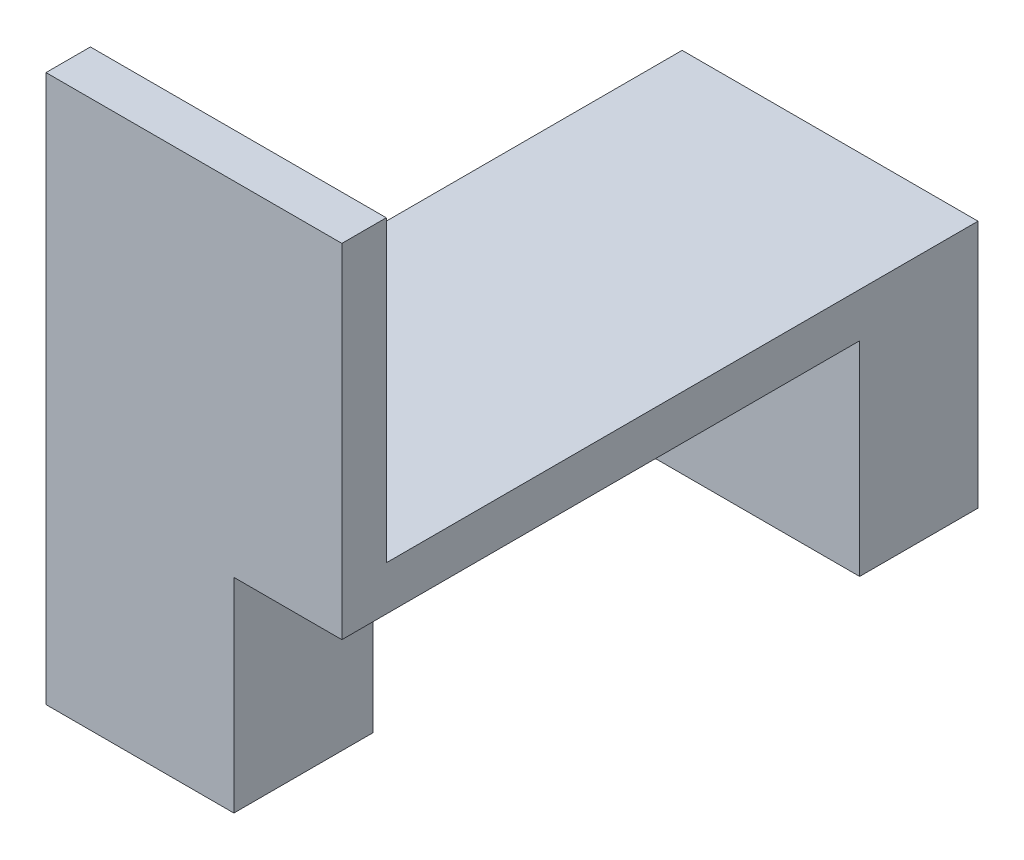
SolidWorks part; units mm, degrees
ref_plane "Спереди" through (0, 0, 0) normal (0, 0, 1) x (1, 0, 0)
ref_plane "Сверху" through (0, 0, 0) normal (0, 1, 0) x (1, 0, 0)
ref_plane "Справа" through (0, 0, 0) normal (1, 0, 0) x (0, 0, -1)
sketch "Эскиз3" plane through (0, 0, 0) normal (1, 0, 0) x (0, 0, -1)
  line L0 (0, 0) -> (-21.5, 0)
  line L1 (-21.5, 0) -> (-21.5, 11.6)
  line L2 (0, 1.5) -> (-20, 1.5)
  line L3 (-20, 1.5) -> (-20, 11.6)
  line L4 (-21.5, 11.6) -> (-20, 11.6)
  line L5 (0, 1.5) -> (0, 0)
  line L6 (-66.5, 11.6) -> (-13.06, 11.6) construction
  point P2 (-21.5, 11.6)
  dimension "D2" = 20
  dimension "D3" = 1.5
extrude "Бобышка-Вытянуть3" add sketch "Эскиз3" against normal blind 10
sketch "Эскиз4" plane through (0, 0, 0) normal (0, 1, 0) x (1, 0, 0)
  line L0 (-10, 0) -> (0, 0) construction
  line L1 (-10, -21.5) -> (-7.5, -21.5)
  line L2 (-10, -21.5) -> (-10, 0)
  line L3 (-10, 0) -> (-7.5, 0)
  line L4 (-7.5, -21.5) -> (-7.5, 0)
  line L5 (-7.3, -4) -> (-7.3, -16.8) construction
  line L6 (-10, -10.75) -> (0, -10.75) construction
  line L7 (0, 0) -> (0, -20) construction
  point P7 (-7.5, -10.75)
  dimension "D1" = 0.2
extrude "Бобышка-Вытянуть4" add sketch "Эскиз4" against normal blind 1.5
sketch "Эскиз5" plane through (0, 0, 0) normal (0, 1, 0) x (1, 0, 0)
  line L0 (0, -4) -> (-7.3, -4) construction
  line L1 (-7.5, 0) -> (-3.65, 0)
  line L2 (-7.5, 0) -> (-7.5, -4) construction
  line L3 (-7.5, -4) -> (-3.65, -4)
  line L4 (-3.65, 0) -> (-3.65, -4) construction
  line L5 (-7.3, -16.8) -> (0, -16.8) construction
  line L6 (-7.5, -21.5) -> (-3.65, -21.5)
  line L7 (-7.5, -21.5) -> (-7.5, -16.8) construction
  line L8 (-7.5, -16.8) -> (-3.65, -16.8)
  line L9 (-3.65, -21.5) -> (-3.65, -16.8)
  line L10 (-7.5, 0) -> (-10, 0)
  line L11 (-10, 0) -> (-10, -4.75)
  line L12 (-10, 0) -> (-10, -21.5) construction
  line L13 (-11.3, -4.75) -> (-7.3, -4.75) construction
  line L14 (-10, -4.75) -> (-7.5, -4.75)
  line L15 (-7.5, -21.5) -> (-7.5, 0) construction
  line L16 (-7.5, -4.75) -> (-7.5, -4)
  line L17 (-7.5, -21.5) -> (-10, -21.5)
  line L18 (-10, -21.5) -> (-10, -16.05)
  line L19 (-11.3, -16.05) -> (-7.3, -16.05) construction
  line L20 (-10, -16.05) -> (-7.5, -16.05)
  line L21 (-7.5, -16.05) -> (-7.5, -16.8)
  line L22 (-3.65, -4) -> (0, -4)
  line L23 (0, -21.5) -> (0, 0) construction
  line L24 (0, -4) -> (0, 0)
  line L25 (0, 0) -> (-3.65, 0)
  circle A0 centre (-5.8, -7.15) radius 0.85
  circle A1 centre (-5.8, -13.65) radius 0.85
  point P29 (-5.8, -7.15)
  point P31 (-5.8, -13.65)
  dimension "D1" = 1.7
extrude "Бобышка-Вытянуть5" add sketch "Эскиз5" against normal up to vertex (6.9 mm away)
sketch "Эскиз6" plane through (0, 0, 0) normal (0, -1, 0) x (1, 0, 0)
  line L1 (-7.5, 4) -> (-3.65, 4)
  line L2 (-7.5, 4) -> (-7.5, 16.8)
  line L3 (-7.5, 16.8) -> (-3.65, 16.8)
  line L4 (-3.65, 4) -> (-3.65, 16.8)
extrude "Вырез-Вытянуть1" cut sketch "Эскиз6" along normal through all from offset 2
